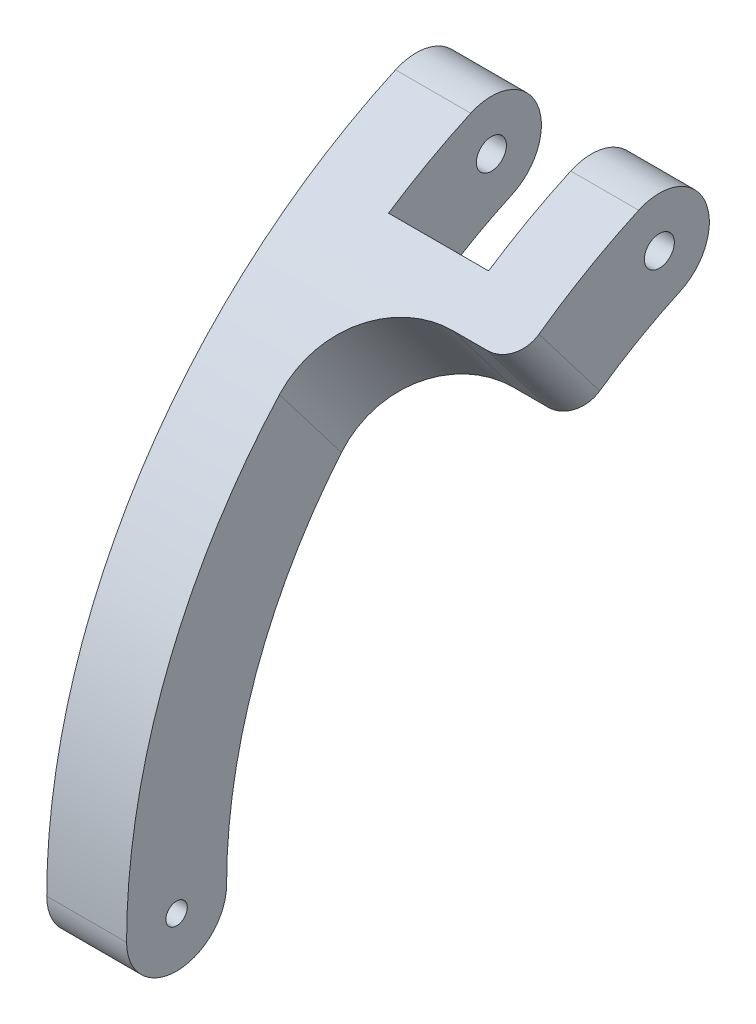
SolidWorks part; units mm, degrees
material "ABS"
ref_plane "Front Plane" through (0, 0, 0) normal (0, 0, 1) x (1, 0, 0)
ref_plane "Top Plane" through (0, 0, 0) normal (0, 1, 0) x (1, 0, 0)
ref_plane "Right Plane" through (0, 0, 0) normal (1, 0, 0) x (0, 0, -1)
sketch "Esquisse1" plane through (0, 0, 0) normal (1, 0, 0) x (0, 0, -1)
  arc A0 (-34.6, 0) -> (-14.2965, 31.5082) centre (0, 0) cw
  arc A1 (-41.6, 0) -> (-17.1889, 37.8827) centre (0, 0) cw
  arc A2 (-41.6, 0) -> (-34.6, 0) centre (-38.1, 0) ccw
  arc A3 (-14.2965, 31.5082) -> (-17.1889, 37.8827) centre (-15.7427, 34.6955) ccw
  circle A4 centre (-38.1, 0) radius 0.75
  circle A5 centre (-15.7427, 34.6955) radius 1.05
  dimension "D1" = 3.5
  dimension "D4" = 1.5
  dimension "D5" = 2.1
  dimension "D2" = 41.275
  dimension "D3" = 38.1
extrude "Boss.-Extru.1" add sketch "Esquisse1" along normal blind 5.588
sketch "Esquisse2" plane through (5.588, 0, 0) normal (1, 0, 0) x (0, 0, -1)
  line L0 (-21.5151, 27.0972) -> (-25.7659, 32.6601)
  arc A0 (-14.2965, 31.5082) -> (-34.6, 0) centre (0, 0) ccw construction
  arc A1 (-17.1889, 37.8827) -> (-41.6, 0) centre (0, 0) ccw construction
  arc A2 (-14.2965, 31.5082) -> (-17.1889, 37.8827) centre (-15.7427, 34.6955) ccw construction
  arc A3 (-14.2965, 31.5082) -> (-21.5151, 27.0972) centre (0, 0) ccw
  arc A4 (-14.2965, 31.5082) -> (-17.1889, 37.8827) centre (-15.7427, 34.6955) ccw
  arc A5 (-17.1889, 37.8827) -> (-25.7659, 32.6601) centre (0, 0) ccw
  dimension "D1" = 9.2
extrude "Boss.-Extru.2" add sketch "Esquisse2" along normal blind 11.43
ref_plane "Plan1" through (8.763, 0, 0) normal (1, 0, 0) x (0, 0, -1)
sketch "Esquisse4" plane through (8.763, 0, 0) normal (1, 0, 0) x (0, 0, -1)
  line L0 (-22.9402, 34.7031) -> (-19.0801, 28.8637)
  arc A0 (-14.2965, 31.5082) -> (-34.6, 0) centre (0, 0) ccw construction
  arc A1 (-14.2965, 31.5082) -> (-17.1889, 37.8827) centre (-15.7427, 34.6955) ccw construction
  arc A2 (-17.1889, 37.8827) -> (-41.6, 0) centre (0, 0) ccw construction
  arc A3 (-14.2965, 31.5082) -> (-19.0801, 28.8637) centre (0, 0) ccw
  arc A4 (-14.2965, 31.5082) -> (-17.1889, 37.8827) centre (-15.7427, 34.6955) ccw
  arc A5 (-17.1889, 37.8827) -> (-22.9402, 34.7031) centre (0, 0) ccw
  dimension "D1" = 6
extrude "Enlèv. mat.-Extru.1" cut sketch "Esquisse4" against normal blind 3.5 and the other way blind 3.5
fillet "Congé1" radius 7 1 edges at (5.588, 29.8787, 23.6405)
fillet "Congé2" radius 2 1 edges at (17.018, 29.8787, 23.6405)
sketch "Esquisse5" plane through (0, 0, 0) normal (-1, 0, 0) x (0, 0, 1)
  circle A0 centre (15.7427, 34.6955) radius 1.05
  circle A1 centre (15.7427, 34.6955) radius 1.05 construction
extrude "Enlèv. mat.-Extru.2" cut sketch "Esquisse5" against normal through all
